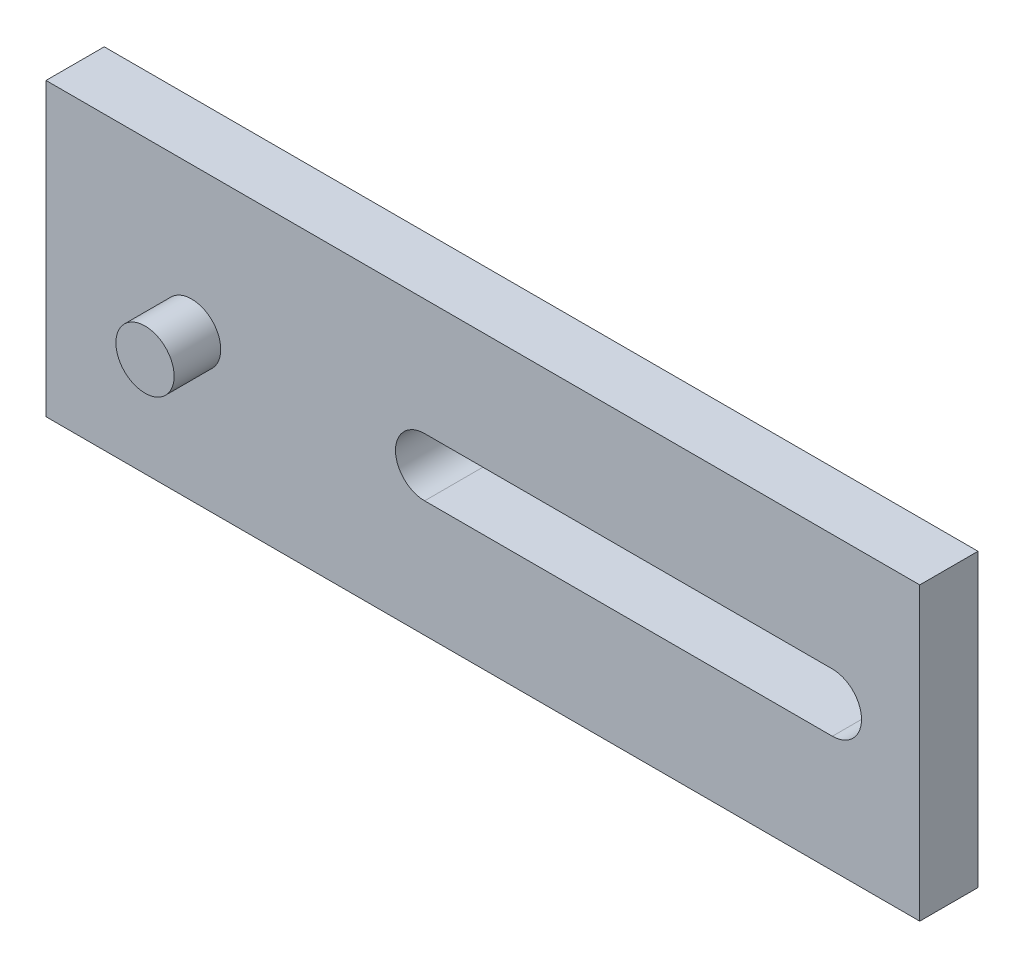
SolidWorks part; units mm, degrees
ref_plane "Plan de face" through (0, 0, 0) normal (0, 0, 1) x (1, 0, 0)
ref_plane "Plan de dessus" through (0, 0, 0) normal (0, 1, 0) x (1, 0, 0)
ref_plane "Plan de droite" through (0, 0, 0) normal (1, 0, 0) x (0, 0, -1)
sketch "Croquis3" plane through (0, 0, 0) normal (0, 0, 1) x (1, 0, 0)
  line L0 (60, 5) -> (-10, 5)
  line L1 (75, -25) -> (-75, -25)
  line L2 (75, -25) -> (75, 25)
  line L3 (75, 25) -> (-75, 25)
  line L4 (-75, -25) -> (-75, 25)
  line L5 (75, -25) -> (-75, 25) construction
  line L6 (75, 25) -> (-75, -25) construction
  line L7 (-10, -5) -> (60, -5)
  arc A0 (60, -5) -> (60, 5) centre (60, 0) ccw
  arc A1 (-10, 5) -> (-10, -5) centre (-10, 0) ccw
  point P0 (0, 0)
  dimension "D7" = 10
  dimension "D1" = 150
  dimension "D2" = 50
  dimension "D3" = 65
  dimension "D4" = 15
  dimension "D5" = 25
  dimension "D6" = 25
extrude "Saliente-Extruir3" add sketch "Croquis3" along normal blind 10
sketch "Croquis4" plane through (0, 0, 10) normal (0, 0, 1) x (1, 0, 0)
  line L0 (-75, -25) -> (75, -25) construction
  line L2 (-75, 25) -> (-75, -25) construction
  circle A0 centre (-50, 0) radius 5
  point P6 (-75, 5.51)
  point P7 (-88.603, 11.9722)
  dimension "D1" = 10
  dimension "D2" = 25
  dimension "D3" = 25
extrude "Saliente-Extruir4" add sketch "Croquis4" along normal blind 8
